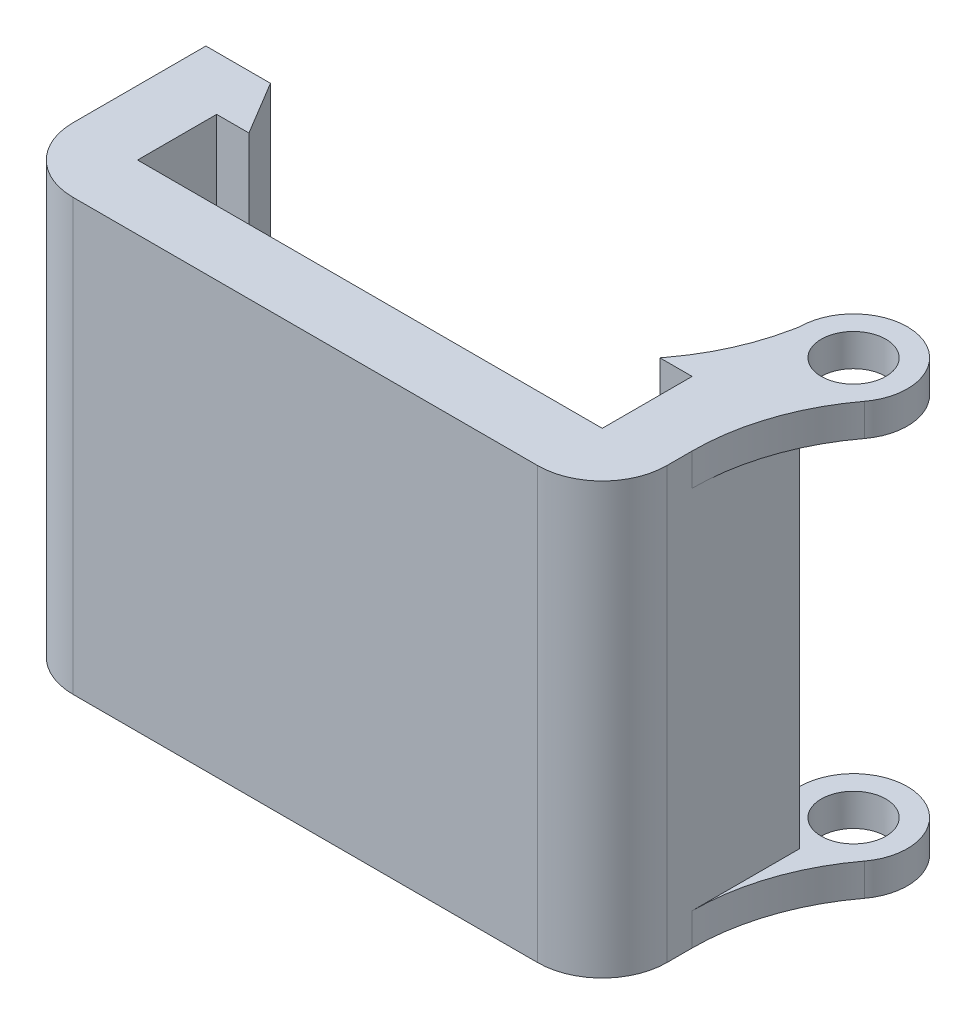
SolidWorks part; units mm, degrees
ref_plane "Front Plane" through (0, 0, 0) normal (0, 0, 1) x (1, 0, 0)
ref_plane "Top Plane" through (0, 0, 0) normal (0, 1, 0) x (1, 0, 0)
ref_plane "Right Plane" through (0, 0, 0) normal (1, 0, 0) x (0, 0, -1)
sketch "Sketch1" plane through (0, 0, 24.175) normal (0, 0, 1) x (1, 0, 0)
  line L0 (-13.795, 75.7847) -> (13.795, 75.7847)
  line L1 (-13.795, 55.7847) -> (13.795, 55.7847)
  line L2 (-13.795, 55.7847) -> (-13.795, 75.7847)
  line L3 (13.795, 55.7847) -> (13.795, 75.7847)
  line L4 (-10.795, 23.495) -> (-10.795, 95.5796) construction
  arc A0 (-3.0486, 76.9696) -> (-76.9008, 4.46) centre (0, 0) ccw construction
  arc A1 (76.9696, 3.0486) -> (4.46, 76.9008) centre (0, 0) ccw construction
  dimension "D1" = 3
  dimension "D2" = 20
extrude "Boss-Extrude1" add sketch "Sketch1" along normal blind 3
sketch "Sketch2" plane through (0, 0, 24.175) normal (0, 0, -1) x (-1, 0, 0)
  line L0 (13.795, 55.7847) -> (-13.795, 55.7847) construction
  line L1 (-13.795, 75.7847) -> (-10.795, 75.7847)
  line L2 (-13.795, 75.7847) -> (-13.795, 55.7847)
  line L3 (-13.795, 55.7847) -> (-10.795, 55.7847)
  line L4 (-10.795, 75.7847) -> (-10.795, 55.7847)
  line L6 (13.795, 75.7847) -> (10.795, 75.7847)
  line L7 (13.795, 75.7847) -> (13.795, 55.7847)
  line L8 (13.795, 55.7847) -> (10.795, 55.7847)
  line L9 (10.795, 75.7847) -> (10.795, 55.7847)
  dimension "D1" = 3
  dimension "D2" = 3
extrude "Boss-Extrude2" add sketch "Sketch2" along normal offset from surface (6.175 mm away) 3
sketch "Sketch4" plane through (0, 75.7847, 0) normal (0, 1, 0) x (1, 0, 0)
  line L0 (-10.795, -20.5) -> (-10.795, -18)
  line L1 (10.795, -18) -> (10.795, -20)
  line L2 (-10.795, -18) -> (-9.295, -20.5)
  line L3 (-9.295, -20.5) -> (-10.795, -20.5)
  line L4 (-10.795, -18) -> (-10.795, -24.175) construction
  line L5 (142.875, -21) -> (-142.875, -21) construction
  line L6 (10.795, -18) -> (10.795, -24.175) construction
  line L7 (10.795, -20) -> (9.295, -20)
  line L8 (9.295, -20) -> (10.795, -18)
  line L9 (10.9665, -21) -> (-10.9664, -21) construction
  dimension "D1" = 1.5
  dimension "D2" = 0.5
  dimension "D3" = 1.5
  dimension "D4" = 1
extrude "Boss-Extrude3" add sketch "Sketch4" against normal up to surface (20 mm away) up to face at (0, 55.7847, 21.8375)
sketch "Sketch5" plane through (0, 0, 27.175) normal (0, 0, 1) x (1, 0, 0)
  line L0 (-13.795, 55.7847) -> (13.795, 55.7847) construction
  line L1 (13.795, 75.7847) -> (8.795, 75.7847)
  line L2 (13.795, 75.7847) -> (13.795, 55.7847)
  line L3 (13.795, 55.7847) -> (8.795, 55.7847)
  line L4 (8.795, 75.7847) -> (8.795, 55.7847)
  dimension "D1" = 5
extrude "Boss-Extrude4" [suppressed] add sketch "Sketch5" along normal blind 6
sketch "Sketch6" plane through (0, 55.7847, 0) normal (0, -1, 0) x (1, 0, 0)
  line L0 (13.795, 18) -> (10.795, 18) construction
  line L1 (13.795, 18) -> (13.795, 15.5) construction
  line L2 (10.795, 18) -> (11.295, 15.5)
  line L3 (10.795, 18) -> (13.795, 18)
  arc A0 (11.295, 15.5) -> (13.795, 18) centre (13.795, 15.5) ccw
  dimension "D1" = 5
extrude "Boss-Extrude5" add sketch "Sketch6" against normal blind 1.5
sketch "Sketch7" plane through (0, 75.7847, 0) normal (0, 1, 0) x (1, 0, 0)
  line L0 (10.795, -18) -> (11.295, -15.5)
  line L1 (10.795, -18) -> (13.795, -18)
  circle A0 centre (13.795, -15.5) radius 2.5 construction
  arc A1 (13.795, -18) -> (11.295, -15.5) centre (13.795, -15.5) ccw
extrude "Boss-Extrude6" add sketch "Sketch7" against normal blind 1.5
sketch "Sketch8" plane through (0, 75.7847, 0) normal (0, 1, 0) x (1, 0, 0)
  circle A0 centre (13.795, -15.5) radius 1.5
  circle A1 centre (13.795, -15.5) radius 1 construction
  dimension "D1" = 0.5
extrude "Cut-Extrude1" cut sketch "Sketch8" against normal up to surface (20 mm away)
sketch "Sketch9" [suppressed] plane through (13.795, 0, 0) normal (1, 0, 0) x (0, 0, -1)
  line L0 (-33.175, 55.7847) -> (-33.175, 75.7847) construction
  line L1 (-33.175, 74.2847) -> (-15, 74.2847)
  line L2 (-33.175, 74.2847) -> (-33.175, 57.2847)
  line L3 (-33.175, 57.2847) -> (-15, 57.2847)
  line L4 (-15, 74.2847) -> (-15, 57.2847)
  dimension "D1" = 18.175
  dimension "D2" = 17
extrude "Cut-Extrude2" [suppressed] cut sketch "Sketch9" against normal blind 1
fillet "Fillet1" radius 10 2 edges at (13.795, 56.5347, 18) (13.795, 75.0347, 18)
fillet "Fillet2" radius 10 2 edges at (10.795, 56.5347, 18) (10.795, 75.0347, 18)
fillet "Fillet3" [suppressed] radius 3
fillet "Fillet4" radius 3 2 edges at (-13.795, 65.7847, 27.175) (13.795, 65.7847, 27.175)
